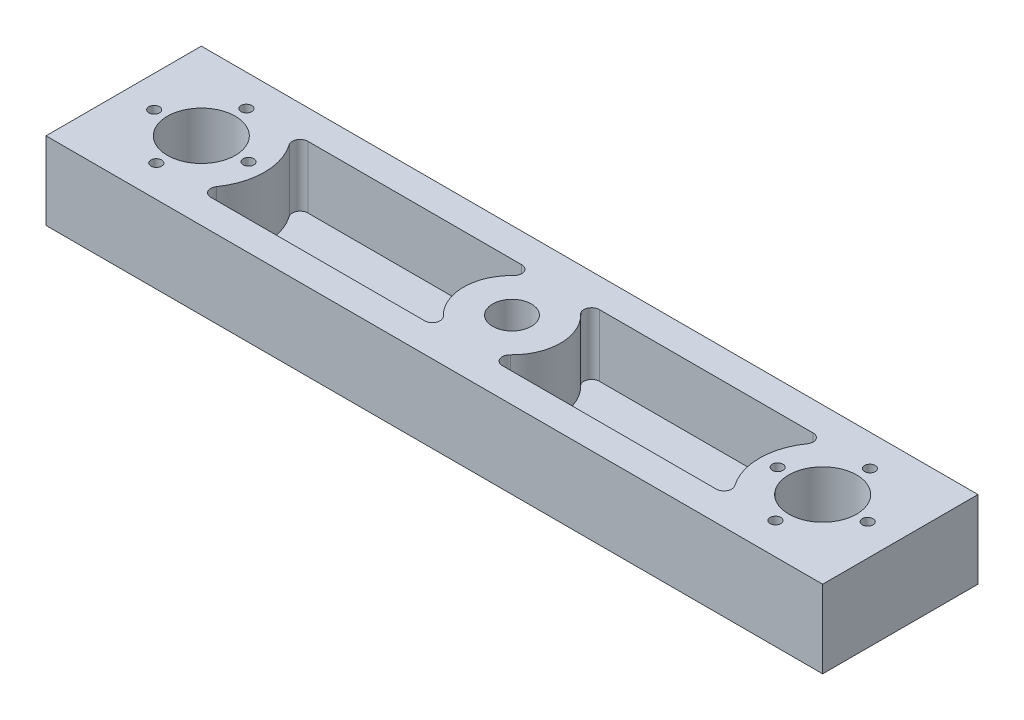
SolidWorks part; units mm, degrees
material "6061-T6 (SS)"
ref_plane "Front Plane" through (0, 0, 0) normal (0, 0, 1) x (1, 0, 0)
ref_plane "Top Plane" through (0, 0, 0) normal (0, 1, 0) x (1, 0, 0)
ref_plane "Right Plane" through (0, 0, 0) normal (1, 0, 0) x (0, 0, -1)
sketch "Sketch2" plane through (0, 0, 0) normal (0, 1, 0) x (1, 0, 0)
  line L0 (0, 0) -> (254, 0)
  line L1 (254, 0) -> (254, 50.8)
  line L2 (254, 50.8) -> (0, 50.8)
  line L3 (0, 50.8) -> (0, 0)
  dimension "D1" = 254
  dimension "D2" = 50.8
extrude "Boss-Extrude1" add sketch "Sketch2" along normal blind 25.4
sketch "Sketch3" plane through (0, 25.4, 0) normal (0, 1, 0) x (1, 0, 0)
  line L0 (0, 25.4) -> (254, 25.4) construction
  line L1 (0, 50.8) -> (0, 0) construction
  line L2 (254, 0) -> (254, 50.8) construction
  circle A0 centre (25.4, 25.4) radius 11.1125
  circle A1 centre (228.6, 25.4) radius 11.1125
  circle A2 centre (127, 25.4) radius 6.35
  point P10 (127, 25.4)
  dimension "D3" = 22.225
  dimension "D4" = 12.7
  dimension "D1" = 203.2
extrude "Cut-Extrude1" cut sketch "Sketch3" against normal through all
sketch "Sketch4" plane through (0, 25.4, 0) normal (0, 1, 0) x (1, 0, 0)
  line L0 (127, 50.8) -> (127, 0) construction
  line L2 (0, 0) -> (254, 0) construction
  point P0 (10.3188, 25.0457)
  point P5 (10.3188, 25.0457)
  point P6 (10.3188, 25.0457)
  point P7 (10.3188, 25.0457)
  point P8 (243.6813, 25.0457)
  point P12 (243.6812, 25.0457)
  point P13 (243.6813, 25.0457)
  point P14 (243.6813, 25.0457)
  dimension "D1" = 15.0812
hole_wizard "#6-32 Tapped Hole1" positions "Sketch4" profile "Sketch5" tap size "#6-32" standard "ANSI Inch" end condition through all
sketch "Sketch5" plane through (10.3188, 25.4, -25.0457) normal (1, 0, 0) x (0, 0, 1)
  line L0 (0, 0) -> (0, 25.4)
  line L1 (0, 25.4) -> (1.7526, 25.4)
  line L2 (1.7526, 25.4) -> (1.7526, 0)
  line L5 (1.7526, 0) -> (0, 0)
  line L11 (0, -6.35) -> (0, 107.95) construction
  dimension "Thread Major Dia." = 3.5052
  dimension "Thru Tap Drill Depth" = 25.4
sketch "Sketch6" plane through (0, 25.4, 0) normal (0, 1, 0) x (1, 0, 0)
  line L4 (44.3572, 41.275) -> (114.3, 41.275)
  line L5 (254, 50.8) -> (0, 50.8) construction
  line L6 (44.3572, 9.525) -> (114.3, 9.525)
  line L7 (0, 0) -> (254, 0) construction
  line L8 (209.6428, 41.275) -> (139.7, 41.275)
  line L9 (209.6428, 9.525) -> (139.7, 9.525)
  arc A0 (42.2797, 37.2736) -> (42.2797, 13.5264) centre (25.4, 25.4) cw
  arc A1 (211.7203, 37.2736) -> (211.7203, 13.5264) centre (228.6, 25.4) ccw
  circle A2 centre (25.4, 25.4) radius 11.1125 construction
  circle A3 centre (228.6, 25.4) radius 11.1125 construction
  arc A4 (116.0517, 36.8957) -> (116.0517, 13.9043) centre (127, 25.4) ccw
  circle A5 centre (127, 25.4) radius 6.35 construction
  arc A6 (137.9483, 36.8957) -> (137.9483, 13.9043) centre (127, 25.4) cw
  arc A7 (42.2797, 37.2736) -> (44.3572, 41.275) centre (44.3572, 38.735) cw
  arc A8 (44.3572, 9.525) -> (42.2797, 13.5264) centre (44.3572, 12.065) cw
  arc A9 (211.7203, 13.5264) -> (209.6428, 9.525) centre (209.6428, 12.065) cw
  arc A10 (211.7203, 37.2736) -> (209.6428, 41.275) centre (209.6428, 38.735) ccw
  arc A11 (137.9483, 36.8957) -> (139.7, 41.275) centre (139.7, 38.735) cw
  arc A12 (137.9483, 13.9043) -> (139.7, 9.525) centre (139.7, 12.065) ccw
  arc A13 (114.3, 41.275) -> (116.0517, 36.8957) centre (114.3, 38.735) cw
  arc A14 (114.3, 9.525) -> (116.0517, 13.9043) centre (114.3, 12.065) ccw
  point P39 (127, 41.275)
  point P42 (127, 9.525)
  dimension "D7" = 2.54
  dimension "D3" = 9.525
  dimension "D4" = 9.525
  dimension "D1" = 9.525
  dimension "D5" = 9.525
  dimension "D2" = 9.525
  dimension "D6" = 9.525
extrude "Cut-Extrude3" cut sketch "Sketch6" against normal blind 20.32
pattern_circular "CirPattern1" count 4 over 360 about axis through (25.4, 0, -25.4) along (0, 1, 0) of "#6-32 Tapped Hole1"
pattern_circular "CirPattern2" count 4 over 360 about axis through (228.6, 0, -25.4) along (0, 1, 0) of "#6-32 Tapped Hole1"
equation "\"CH_length\"= 10"
equation "\"CH_width\"= 2"
equation "\"CH_height\"= 1"
equation "\"CtC_distance\"= 8"
equation "\"D2@Sketch2\"=\"CH_width\""
equation "\"D1@Sketch2\"=\"CH_length\""
equation "\"D1@Boss-Extrude1\"=\"CH_height\""
equation "\"D1@Sketch3\"=\"CtC_distance\""
equation "\"D2@Sketch3\"=\"CtC_distance\"/2"
equation "\"CH_hole_diameter\"= 0.875"
equation "\"D3@Sketch3\"=\"CH_hole_diameter\""
equation "\"D1@Sketch4\"=1.1875/2"
equation "\"Wall_thickness\"= 0.375"
equation "\"D3@Sketch6\"=\"Wall_thickness\""
equation "\"D4@Sketch6\"=\"Wall_thickness\""
equation "\"D1@Sketch6\"=\"Wall_thickness\""
equation "\"D5@Sketch6\"=\"Wall_thickness\""
equation "\"D2@Sketch6\"=\"Wall_thickness\""
equation "\"D6@Sketch6\"=\"Wall_thickness\""
equation "\"D1@Cut-Extrude3\"=\"CH_height\"-.2"
